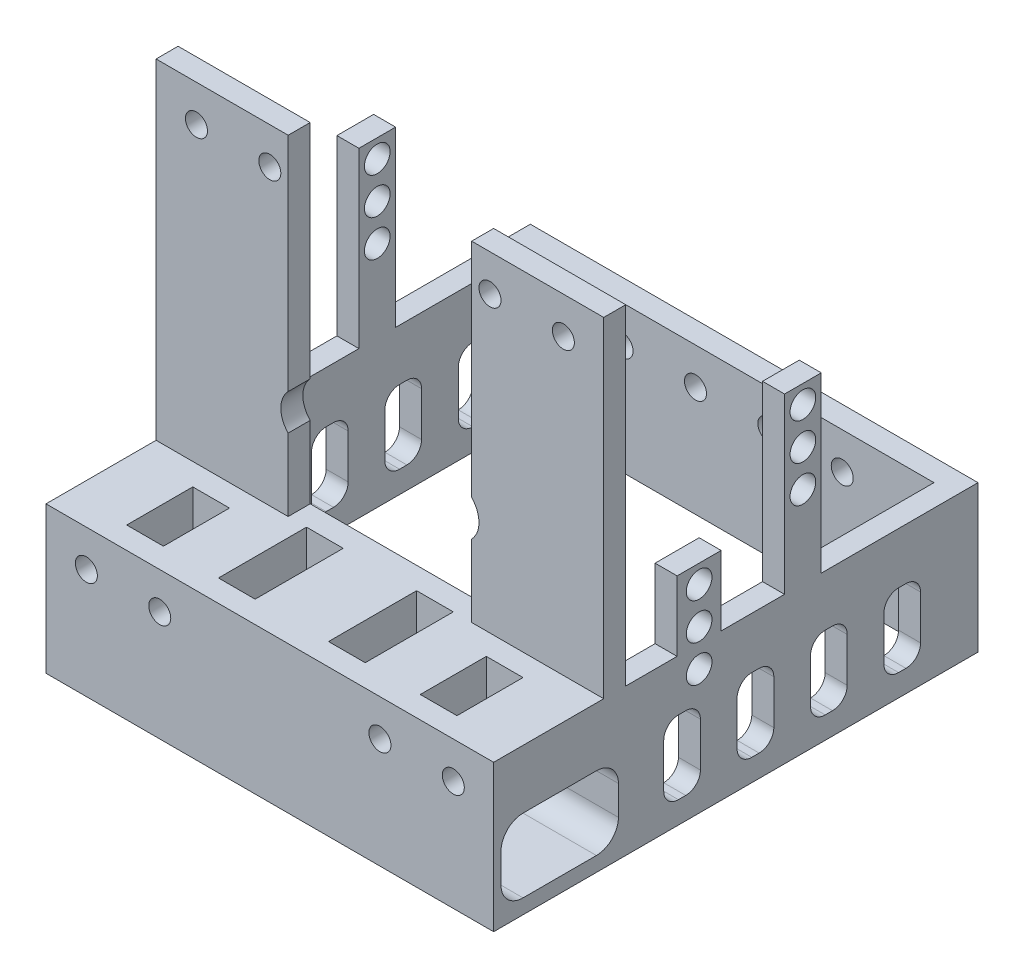
SolidWorks part; units mm, degrees
ref_plane "Front Plane" through (0, 0, 0) normal (0, 0, 1) x (1, 0, 0)
ref_plane "Top Plane" through (0, 0, 0) normal (0, 1, 0) x (1, 0, 0)
ref_plane "Right Plane" through (0, 0, 0) normal (1, 0, 0) x (0, 0, -1)
sketch "Sketch1" plane through (0, 0, 0) normal (0, 0, 1) x (1, 0, 0)
  line L1 (0, 0) -> (-55, 0)
  line L2 (0, 0) -> (0, 10)
  line L3 (0, 10) -> (-55, 10)
  line L4 (-55, 0) -> (-55, 10)
  circle A4 centre (-2.5, 5) radius 1.5
  circle A5 centre (-12.5, 5) radius 1.5
  circle A6 centre (-42.5, 5) radius 1.5
  circle A7 centre (-52.5, 5) radius 1.5
  dimension "D3" = 3
  dimension "D1" = 55
  dimension "D2" = 10
extrude "Boss-Extrude1" add sketch "Sketch1" along normal blind 15
sketch "Sketch2" plane through (0, 0, 0) normal (0, 0, -1) x (-1, 0, 0)
  line L0 (55, 10) -> (55, 0) construction
  line L1 (0, 0) -> (15, 0)
  line L2 (0, 0) -> (0, 55)
  line L3 (0, 55) -> (15, 55)
  line L4 (15, 0) -> (15, 55)
  line L5 (55, 0) -> (40, 0)
  line L6 (55, 0) -> (55, 55)
  line L7 (55, 55) -> (40, 55)
  line L8 (40, 0) -> (40, 55)
  line L9 (15, 0) -> (40, 0)
  line L10 (0, 10) -> (55, 10) construction
  line L11 (0, 10) -> (55, 10)
  circle A0 centre (12.5, 50) radius 1.5 construction
  circle A1 centre (2.5, 50) radius 1.5 construction
  circle A2 centre (2.5, 5) radius 1.5 construction
  circle A3 centre (12.5, 5) radius 1.5 construction
  circle A4 centre (52.5, 5) radius 1.5 construction
  circle A5 centre (42.5, 5) radius 1.5 construction
  circle A6 centre (52.5, 50) radius 1.5 construction
  circle A7 centre (42.5, 50) radius 1.5 construction
  circle A8 centre (12.5, 50) radius 1.5
  circle A9 centre (2.5, 50) radius 1.5
  circle A10 centre (2.5, 5) radius 1.5
  circle A11 centre (12.5, 5) radius 1.5
  circle A12 centre (52.5, 5) radius 1.5
  circle A13 centre (42.5, 5) radius 1.5
  circle A14 centre (52.5, 50) radius 1.5
  circle A15 centre (42.5, 50) radius 1.5
  circle A16 centre (17.5, 22.3) radius 3.5
  circle A17 centre (37.5, 22.3) radius 3.5
  line M9 (0, 10) -> (0, 0)
  line M10 (0, 0) -> (55, 0)
  line M11 (55, 0) -> (55, 10)
  line M12 (55, 10) -> (0, 10)
  circle M13 centre (2.5, 5) radius 1.5
  circle M14 centre (12.5, 5) radius 1.5
  circle M15 centre (42.5, 5) radius 1.5
  circle M16 centre (52.5, 5) radius 1.5
extrude "Boss-Extrude2" add sketch "Sketch2" along normal blind 3 contours L8 L4 M10 M12 | A16 L4 L3 L2 A9 A8 M12 | L4 M10 M12 M9 M14 M13 | L8 M10 M11 M12 M15 M16 | A17 L8 L6 L7 A15 A14 M12
sketch "Sketch3" plane through (0, 0, 0) normal (0, -1, 0) x (1, 0, 0)
  line L4 (-55, 15) -> (-55, -3)
  line L5 (-55, -3) -> (0, -3)
  line L6 (0, -3) -> (0, 15)
  line L7 (0, 15) -> (-55, 15)
  line L8 (-55, 15) -> (-55, -3)
  line L9 (-55, -3) -> (0, -3)
  line L10 (0, -3) -> (0, 15)
  line L11 (0, 15) -> (-55, 15)
  dimension "D1" = 0
extrude "Boss-Extrude3" add sketch "Sketch3" along normal blind 10
sketch "Sketch6" plane through (0, 0, 0) normal (1, 0, 0) x (0, 0, -1)
  line L6 (-15, 10) -> (-15, -10)
  line L7 (-15, -10) -> (3, -10)
  line L8 (3, -10) -> (3, 55)
  line L9 (3, 55) -> (0, 55)
  line L10 (0, 55) -> (0, 10)
  line L11 (0, 10) -> (-15, 10)
  line L12 (-15, 10) -> (-15, -10)
  line L13 (-15, -10) -> (3, -10)
  line L14 (3, -10) -> (3, 55)
  line L15 (3, 55) -> (0, 55)
  line L16 (0, 55) -> (0, 10)
  line L17 (0, 10) -> (-15, 10)
  dimension "D1" = 0
extrude "Boss-Extrude5" add sketch "Sketch6" along normal blind 3
sketch "Sketch8" plane through (-55, 0, 0) normal (-1, 0, 0) x (0, 0, 1)
  line L6 (15, 10) -> (0, 10)
  line L7 (0, 10) -> (0, 55)
  line L8 (0, 55) -> (-3, 55)
  line L9 (-3, 55) -> (-3, -10)
  line L10 (-3, -10) -> (15, -10)
  line L11 (15, -10) -> (15, 10)
  line L12 (15, 10) -> (0, 10)
  line L13 (0, 10) -> (0, 55)
  line L14 (0, 55) -> (-3, 55)
  line L15 (-3, 55) -> (-3, -10)
  line L16 (-3, -10) -> (15, -10)
  line L17 (15, -10) -> (15, 10)
  dimension "D1" = 0
extrude "Boss-Extrude6" add sketch "Sketch8" along normal blind 3
sketch "Sketch9" plane through (-58, 0, 0) normal (-1, 0, 0) x (0, 0, 1)
  line L0 (15, -10) -> (15, 10) construction
  line L1 (1, -8) -> (11, -8)
  line L2 (-2, -5) -> (-2, -1)
  line L3 (1, 2) -> (11, 2)
  line L4 (14, -5) -> (14, -1)
  line L5 (-3, 55) -> (-3, -10) construction
  line L6 (-3, -10) -> (15, -10) construction
  arc A0 (1, -8) -> (-2, -5) centre (1, -5) cw
  arc A1 (11, -8) -> (14, -5) centre (11, -5) ccw
  arc A2 (11, 2) -> (14, -1) centre (11, -1) cw
  arc A3 (-2, -1) -> (1, 2) centre (1, -1) cw
  dimension "D5" = 3
  dimension "D1" = 1
  dimension "D2" = 1
  dimension "D3" = 2
  dimension "D4" = 10
extrude "Cut-Extrude2" cut sketch "Sketch9" against normal through all
sketch "Sketch10" plane through (0, 0, -3) normal (0, 0, -1) x (-1, 0, 0)
  line L1 (58, -10) -> (55, -10)
  line L2 (58, -10) -> (58, 10)
  line L3 (58, 10) -> (55, 10)
  line L4 (55, -10) -> (55, 10)
  line L5 (-3, -10) -> (0, -10)
  line L6 (-3, -10) -> (-3, 10)
  line L7 (-3, 10) -> (0, 10)
  line L8 (0, -10) -> (0, 10)
  dimension "D1" = 20
  dimension "D2" = 3
  dimension "D3" = 3
  dimension "D4" = 20
extrude "Boss-Extrude7" add sketch "Sketch10" along normal blind 45
ref_plane "Plane1" through (-27.5, 0, 0) normal (-1, 0, 0) x (0, 0, 1)
sketch "Sketch11" plane through (-58, 0, 0) normal (-1, 0, 0) x (0, 0, 1)
  line L0 (-48, 10) -> (-3, 10) construction
  line L1 (-3, 55) -> (-3, 10) construction
  circle A0 centre (-13, 7) radius 1.75
  dimension "D1" = 3.5
  dimension "D2" = 3
  dimension "D3" = 10
extrude "Cut-Extrude3" cut sketch "Sketch11" against normal through all
sketch "Sketch12" plane through (-58, 0, 0) normal (-1, 0, 0) x (0, 0, 1)
  line L0 (-48, 10) -> (-3, 10) construction
  line L1 (-24.64, 10) -> (-29.64, 10)
  line L2 (-24.64, 10) -> (-24.64, 33.64)
  line L3 (-24.64, 33.64) -> (-29.64, 33.64)
  line L4 (-29.64, 10) -> (-29.64, 33.64)
  line L6 (-10, 10) -> (-16, 10)
  line L7 (-10, 10) -> (-10, 19.5)
  line L8 (-10, 19.5) -> (-16, 19.5)
  line L9 (-16, 10) -> (-16, 19.5)
  circle A0 centre (-27.14, 31.14) radius 1.75
  circle A2 centre (-13, 17) radius 1.75
  circle A3 centre (-13, 7) radius 1.75 construction
  circle A4 centre (-27.14, 26.14) radius 1.75
  circle A6 centre (-27.14, 21.14) radius 1.75
  circle A7 centre (-13, 12) radius 1.75
  dimension "D1" = 3.5
  dimension "D3" = 2.5
  dimension "D4" = 14.14
  dimension "D5" = 14.14
  dimension "D6" = 2.5
  dimension "D7" = 2.5
  dimension "D8" = 3
  dimension "D10" = 10
  dimension "D11" = 5
  dimension "D2" = 5
  dimension "D9" = 6
  dimension "D12" = 2
extrude "Boss-Extrude8" add sketch "Sketch12" against normal blind 3
mirror "Mirror1" about plane through (-27.5, 0, 0) normal (-1, 0, 0) of "Boss-Extrude8"
sketch "Sketch13" plane through (0, 0, -48) normal (0, 0, -1) x (-1, 0, 0)
  line L0 (27.5, -34.65) -> (27.5, 34.65) construction
  line L1 (-3, -10) -> (58, -10)
  line L2 (-3, -10) -> (-3, 10)
  line L3 (-3, 10) -> (58, 10)
  line L4 (58, -10) -> (58, 10)
  circle A0 centre (22.5, 5) radius 1.5
  circle A1 centre (12.5, 5) radius 1.5
  circle A2 centre (2.5, 5) radius 1.5
  circle A3 centre (52.5, 5) radius 1.5
  circle A4 centre (42.5, 5) radius 1.5
  circle A5 centre (32.5, 5) radius 1.5
  dimension "D1" = 3
  dimension "D2" = 5
  dimension "D4" = 5
  dimension "D3" = 3
extrude "Boss-Extrude9" add sketch "Sketch13" along normal blind 3
sketch "Sketch14" plane through (0, 10, 0) normal (0, 1, 0) x (1, 0, 0)
  line L0 (-27.5, 35.75) -> (-27.5, -35.75) construction
  line L1 (-37.5, -12) -> (-32.5, -12)
  line L2 (-37.5, -12) -> (-37.5, 0)
  line L3 (-37.5, 0) -> (-32.5, 0)
  line L4 (-32.5, -12) -> (-32.5, 0)
  line L5 (-50, -3) -> (-45, -3)
  line L6 (-50, -3) -> (-50, -12)
  line L7 (-50, -12) -> (-45, -12)
  line L8 (-45, -3) -> (-45, -12)
  line L9 (3, -15) -> (-58, -15) construction
  line L10 (-40, 0) -> (-58, 0) construction
  line L11 (-40, 3) -> (-15, 3) construction
  line L16 (-17.5, 0) -> (-22.5, 0)
  line L17 (-22.5, -12) -> (-22.5, 0)
  line L18 (-17.5, -12) -> (-22.5, -12)
  line L19 (-17.5, -12) -> (-17.5, 0)
  line L20 (-5, -12) -> (-10, -12)
  line L21 (-10, -3) -> (-10, -12)
  line L22 (-5, -3) -> (-10, -3)
  line L23 (-5, -3) -> (-5, -12)
  dimension "D1" = 5
  dimension "D2" = 5
  dimension "D3" = 7.5
  dimension "D4" = 5
  dimension "D5" = 3
  dimension "D6" = 3
  dimension "D7" = 3
  dimension "D8" = 3
extrude "Cut-Extrude4" cut sketch "Sketch14" against normal blind 10
sketch "Sketch15" plane through (-58, 0, 0) normal (-1, 0, 0) x (0, 0, 1)
  line L0 (-51, -10) -> (15, -10) construction
  line L1 (-10.1761, -7) -> (-11.1761, -7)
  line L2 (-8.1761, -5) -> (-8.1761, 1)
  line L3 (-10.1761, 3) -> (-11.1761, 3)
  line L4 (-13.1761, -5) -> (-13.1761, 1)
  line L5 (-18.1761, -5) -> (-18.1761, 1)
  line L6 (-20.1761, -7) -> (-21.1761, -7)
  line L7 (-23.1761, -5) -> (-23.1761, 1)
  line L8 (-20.1761, 3) -> (-21.1761, 3)
  line L9 (-28.1761, -5) -> (-28.1761, 1)
  line L10 (-30.1761, -7) -> (-31.1761, -7)
  line L11 (-33.1761, -5) -> (-33.1761, 1)
  line L12 (-30.1761, 3) -> (-31.1761, 3)
  line L13 (-38.1761, -5) -> (-38.1761, 1)
  line L14 (-40.1761, -7) -> (-41.1761, -7)
  line L15 (-43.1761, -5) -> (-43.1761, 1)
  line L16 (-40.1761, 3) -> (-41.1761, 3)
  arc A0 (-10.1761, -7) -> (-8.1761, -5) centre (-10.1761, -5) ccw
  arc A1 (-11.1761, -7) -> (-13.1761, -5) centre (-11.1761, -5) cw
  arc A2 (-11.1761, 3) -> (-13.1761, 1) centre (-11.1761, 1) ccw
  arc A3 (-8.1761, 1) -> (-10.1761, 3) centre (-10.1761, 1) ccw
  arc A4 (-18.1761, 1) -> (-20.1761, 3) centre (-20.1761, 1) ccw
  arc A5 (-20.1761, -7) -> (-18.1761, -5) centre (-20.1761, -5) ccw
  arc A6 (-21.1761, -7) -> (-23.1761, -5) centre (-21.1761, -5) cw
  arc A7 (-21.1761, 3) -> (-23.1761, 1) centre (-21.1761, 1) ccw
  arc A8 (-28.1761, 1) -> (-30.1761, 3) centre (-30.1761, 1) ccw
  arc A9 (-30.1761, -7) -> (-28.1761, -5) centre (-30.1761, -5) ccw
  arc A10 (-31.1761, -7) -> (-33.1761, -5) centre (-31.1761, -5) cw
  arc A11 (-31.1761, 3) -> (-33.1761, 1) centre (-31.1761, 1) ccw
  arc A12 (-38.1761, 1) -> (-40.1761, 3) centre (-40.1761, 1) ccw
  arc A13 (-40.1761, -7) -> (-38.1761, -5) centre (-40.1761, -5) ccw
  arc A14 (-41.1761, -7) -> (-43.1761, -5) centre (-41.1761, -5) cw
  arc A15 (-41.1761, 3) -> (-43.1761, 1) centre (-41.1761, 1) ccw
  point P8 (-8.1761, -7)
  point P11 (-13.1761, -7)
  point P16 (-8.1761, 3)
  dimension "D4" = 2
  dimension "D1" = 5
  dimension "D2" = 10
  dimension "D3" = 3
  dimension "D5" = 4
extrude "Cut-Extrude5" cut sketch "Sketch15" against normal through all
